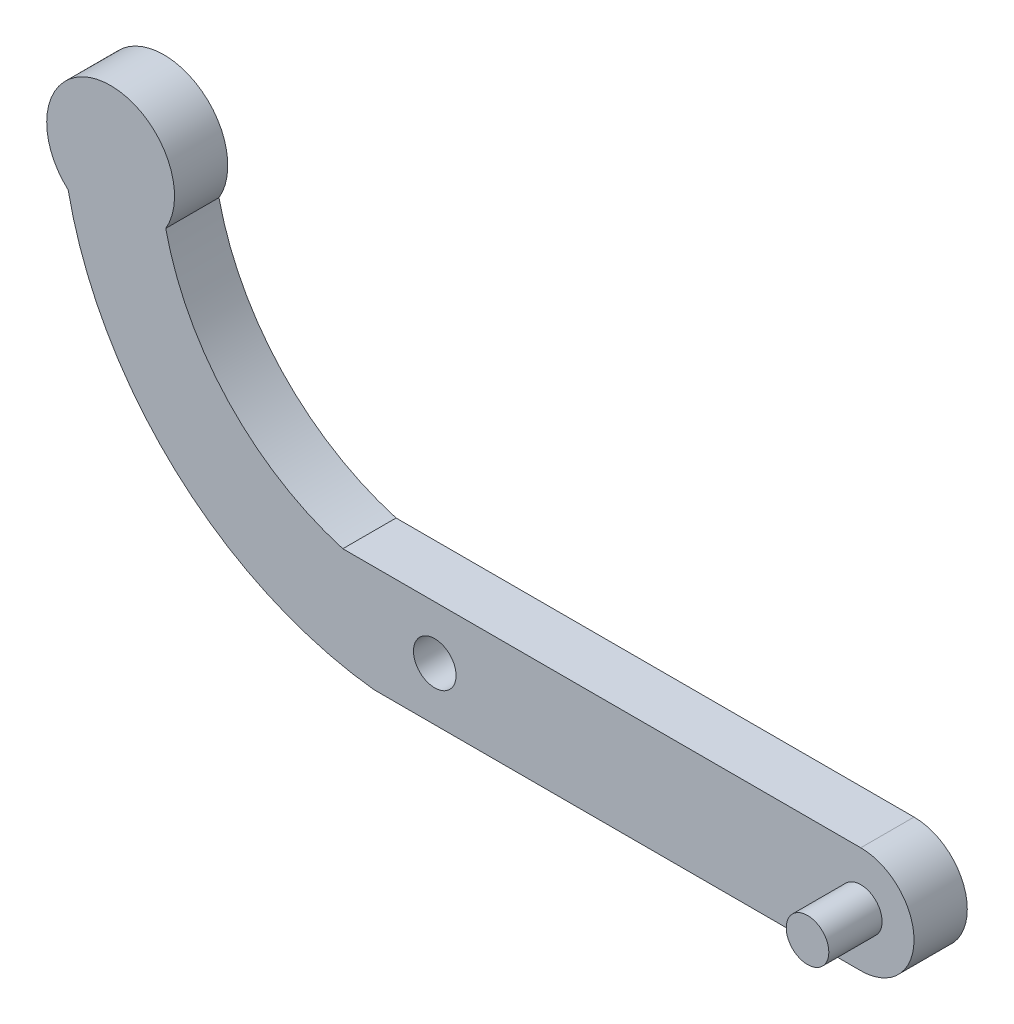
SolidWorks part; units mm, degrees
ref_plane "Alzado" through (0, 0, 0) normal (0, 0, 1) x (1, 0, 0)
ref_plane "Planta" through (0, 0, 0) normal (0, 1, 0) x (1, 0, 0)
ref_plane "Vista lateral" through (0, 0, 0) normal (1, 0, 0) x (0, 0, -1)
sketch "Croquis1" plane through (0, 0, 0) normal (0, 0, 1) x (1, 0, 0)
  line L1 (-25.9537, 5.8047) -> (22.6781, 5.8047)
  line L3 (-23.0472, -4.1953) -> (22.6781, -4.1953)
  arc A1 (22.6781, -4.1953) -> (22.6781, 5.8047) centre (22.6781, 0.8047) ccw
  arc A5 (-42.5787, 23.5412) -> (-25.9537, 5.8047) centre (-19.2925, 28.7084) ccw
  circle A7 centre (-17.3219, 0.8047) radius 2
  arc A8 (-42.5787, 23.5412) -> (-51.7413, 22.0883) centre (-47.7561, 26.5736) ccw
  arc A9 (-51.7413, 22.0883) -> (-23.0472, -4.1953) centre (-19.2925, 28.7084) ccw
  dimension "D2" = 6
  dimension "D3" = 5
  dimension "D6" = 4
  dimension "D7" = 23.8527
  dimension "D8" = 33.1172
  dimension "D1" = 40
  dimension "D5" = 10
  dimension "D9" = 75
extrude "Saliente-Extruir1" add sketch "Croquis1" along normal blind 5
sketch "Croquis2" plane through (0, 0, 5) normal (0, 0, 1) x (1, 0, 0)
  line L0 (-17.3219, 0.8047) -> (22.6781, 0.8047) construction
  circle A0 centre (22.6781, 0.8047) radius 2
  circle A1 centre (-17.3219, 0.8047) radius 2 construction
  point P5 (0, 0)
  dimension "D1" = 4
  dimension "D2" = 40
extrude "Saliente-Extruir2" add sketch "Croquis2" along normal blind 5
